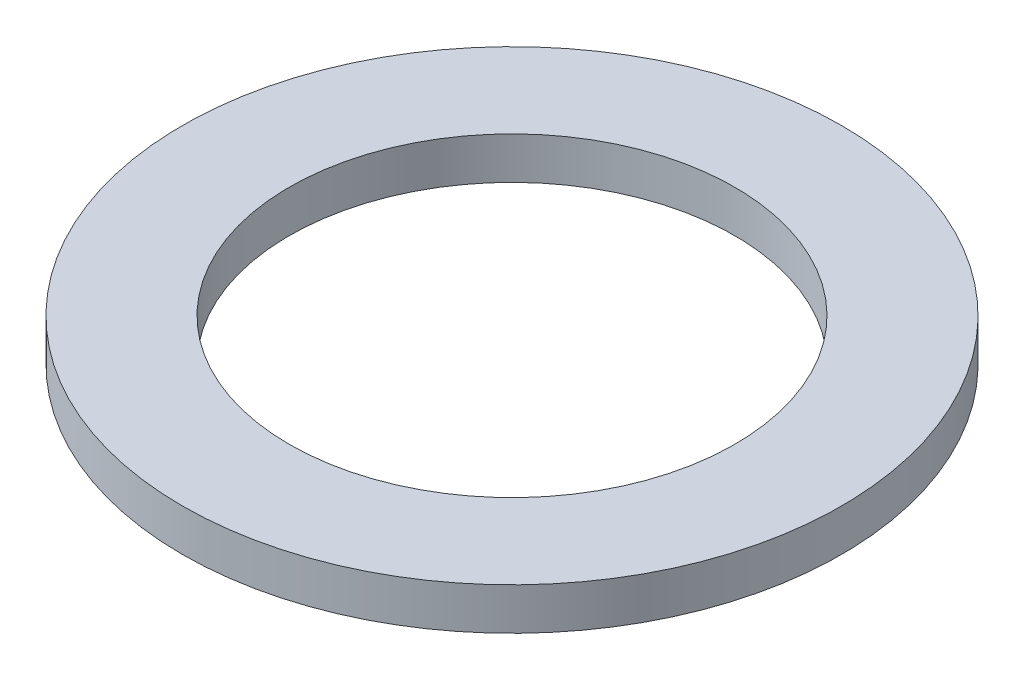
SolidWorks part; units mm, degrees
ref_plane "Front" through (0, 0, 0) normal (0, 0, 1) x (1, 0, 0)
ref_plane "Top" through (0, 0, 0) normal (0, 1, 0) x (1, 0, 0)
ref_plane "Right" through (0, 0, 0) normal (1, 0, 0) x (0, 0, -1)
sketch "Sketch1" plane through (0, 0, 0) normal (0, 1, 0) x (1, 0, 0)
  circle A0 centre (0, 0) radius 26.51
  circle A1 centre (0, 0) radius 39.22
  dimension "D1" = 53.02
  dimension "D2" = 78.44
extrude "Boss-Extrude1" add sketch "Sketch1" along normal blind 5
